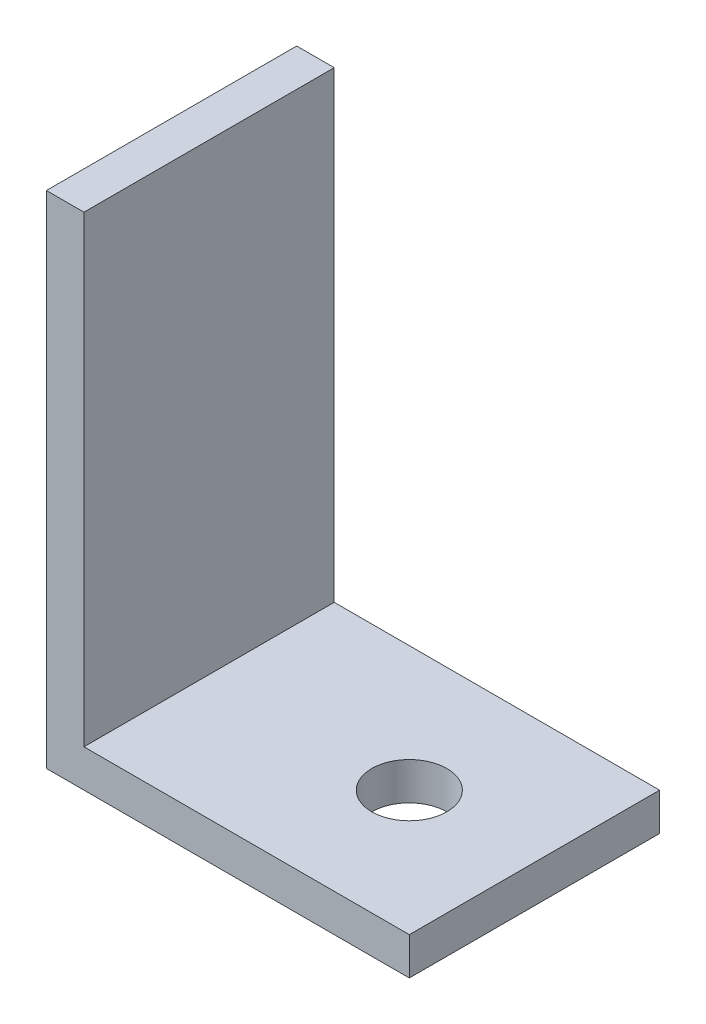
SolidWorks part; units mm, degrees
ref_plane "Front Plane" through (0, 0, 0) normal (0, 0, 1) x (1, 0, 0)
ref_plane "Top Plane" through (0, 0, 0) normal (0, 1, 0) x (1, 0, 0)
ref_plane "Right Plane" through (0, 0, 0) normal (1, 0, 0) x (0, 0, -1)
sketch "Sketch1" plane through (0, 0, 0) normal (0, 0, 1) x (1, 0, 0)
  line L0 (0, 0) -> (0, 40)
  line L1 (0, 40) -> (3, 40)
  line L2 (3, 40) -> (3, 3)
  line L3 (3, 3) -> (29, 3)
  line L4 (29, 3) -> (29, 0)
  line L5 (29, 0) -> (0, 0)
  dimension "D1" = 3
  dimension "D2" = 3
  dimension "D3" = 40
  dimension "D4" = 29
extrude "Boss-Extrude1" add sketch "Sketch1" along normal blind 20
sketch "Sketch2" plane through (0, 3, 0) normal (0, 1, 0) x (1, 0, 0)
  line L0 (0, -20) -> (0, 0) construction
  line L1 (29, -20) -> (29, 0) construction
  circle A0 centre (19, -10) radius 3
  point P4 (0, 0)
  point P7 (29, -10)
  dimension "D1" = 6
  dimension "D2" = 19
extrude "Cut-Extrude1" cut sketch "Sketch2" against normal through all
